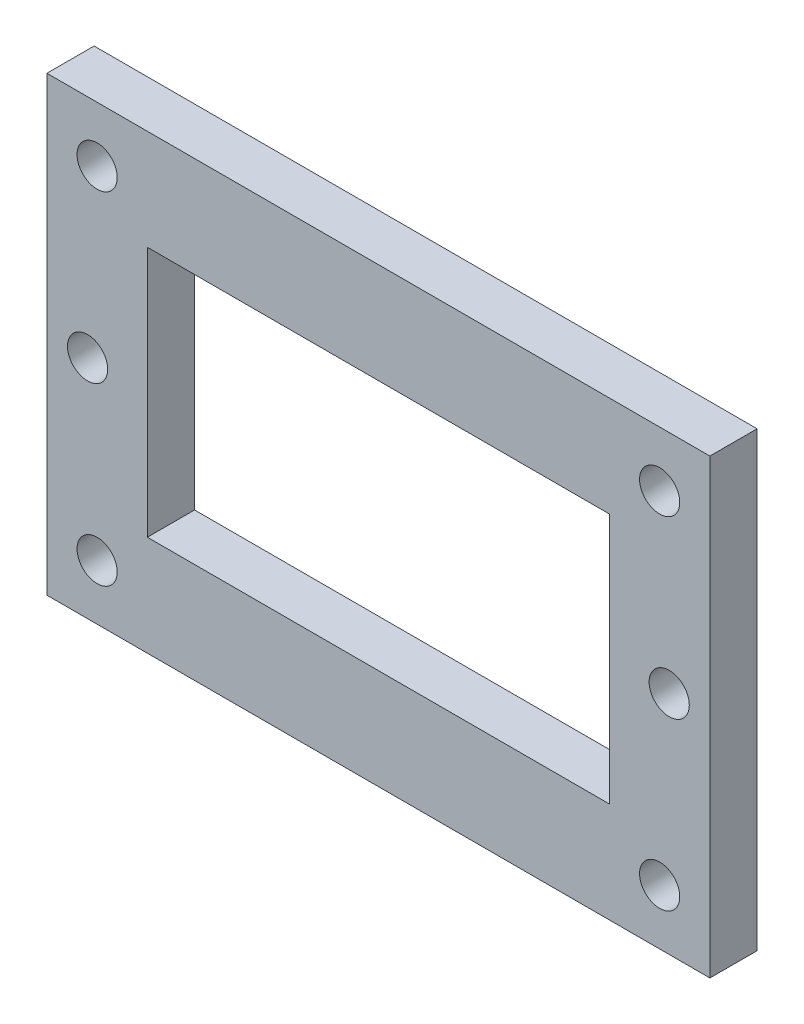
SolidWorks part; units mm, degrees
ref_plane "Piano frontale" through (0, 0, 0) normal (0, 0, 1) x (1, 0, 0)
ref_plane "Piano superiore" through (0, 0, 0) normal (0, 1, 0) x (1, 0, 0)
ref_plane "Piano destro" through (0, 0, 0) normal (1, 0, 0) x (0, 0, -1)
sketch "Schizzo1" plane through (0, 0, 0) normal (0, 0, 1) x (1, 0, 0)
  line L1 (11.5, 6.25) -> (-11.5, 6.25)
  line L2 (11.5, 6.25) -> (11.5, -6.25)
  line L3 (11.5, -6.25) -> (-11.5, -6.25)
  line L4 (-11.5, 6.25) -> (-11.5, -6.25)
  line L5 (11.5, 6.25) -> (-11.5, -6.25) construction
  line L6 (11.5, -6.25) -> (-11.5, 6.25) construction
  line L7 (16.5, 11.25) -> (-16.5, 11.25)
  line L8 (16.5, 11.25) -> (16.5, -11.25)
  line L9 (16.5, -11.25) -> (-16.5, -11.25)
  line L10 (-16.5, 11.25) -> (-16.5, -11.25)
  line L11 (16.5, 11.25) -> (-16.5, -11.25) construction
  line L12 (16.5, -11.25) -> (-16.5, 11.25) construction
  point P0 (0, 0)
  point P6 (0, 0)
  dimension "D1" = 23
  dimension "D2" = 12.5
  dimension "D3" = 5
  dimension "D4" = 5
extrude "Estrusione-Estrusione1" add sketch "Schizzo1" along normal blind 2.35
sketch "Schizzo2" plane through (0, 0, 2.35) normal (0, 0, 1) x (1, 0, 0)
  line L0 (0, 0) -> (-14, 0) construction
  line L1 (-14, 0) -> (-14, 8.5) construction
  circle A0 centre (-14, 8.5) radius 1
  dimension "D3" = 2
  dimension "D1" = 14
  dimension "D2" = 8.5
extrude "Taglio-Estrusione1" cut sketch "Schizzo2" against normal blind 2.35
mirror "Specchia1" about plane through (0, 0, 0) normal (0, 1, 0) of "Taglio-Estrusione1"
mirror "Specchia2" about plane through (0, 0, 0) normal (1, 0, 0) of "Specchia1", "Taglio-Estrusione1"
sketch "Schizzo3" plane through (0, 0, 2.35) normal (0, 0, 1) x (1, 0, 0)
  line L0 (0, 0) -> (14.475, 0) construction
  circle A0 centre (14.475, 0) radius 1
  dimension "D2" = 2
  dimension "D1" = 14.475
extrude "Taglio-Estrusione2" cut sketch "Schizzo3" against normal blind 2.35
mirror "Specchia3" about plane through (0, 0, 0) normal (1, 0, 0) of "Taglio-Estrusione2"
